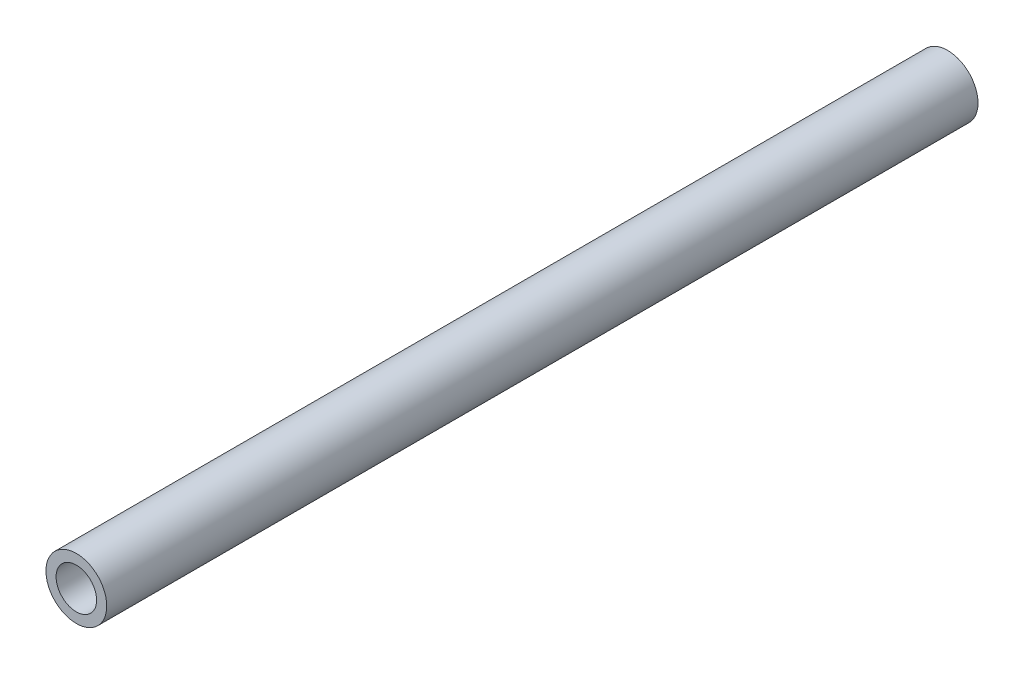
SolidWorks part; units mm, degrees
ref_plane "Спереди" through (0, 0, 0) normal (0, 0, 1) x (1, 0, 0)
ref_plane "Сверху" through (0, 0, 0) normal (0, 1, 0) x (1, 0, 0)
ref_plane "Справа" through (0, 0, 0) normal (1, 0, 0) x (0, 0, -1)
sketch "Эскиз1" plane through (0, 0, 0) normal (0, 0, 1) x (1, 0, 0)
  circle A0 centre (0, 0) radius 2
  circle A1 centre (0, 0) radius 3
extrude "Вытянуть1" add sketch "Эскиз1" along normal blind 86
